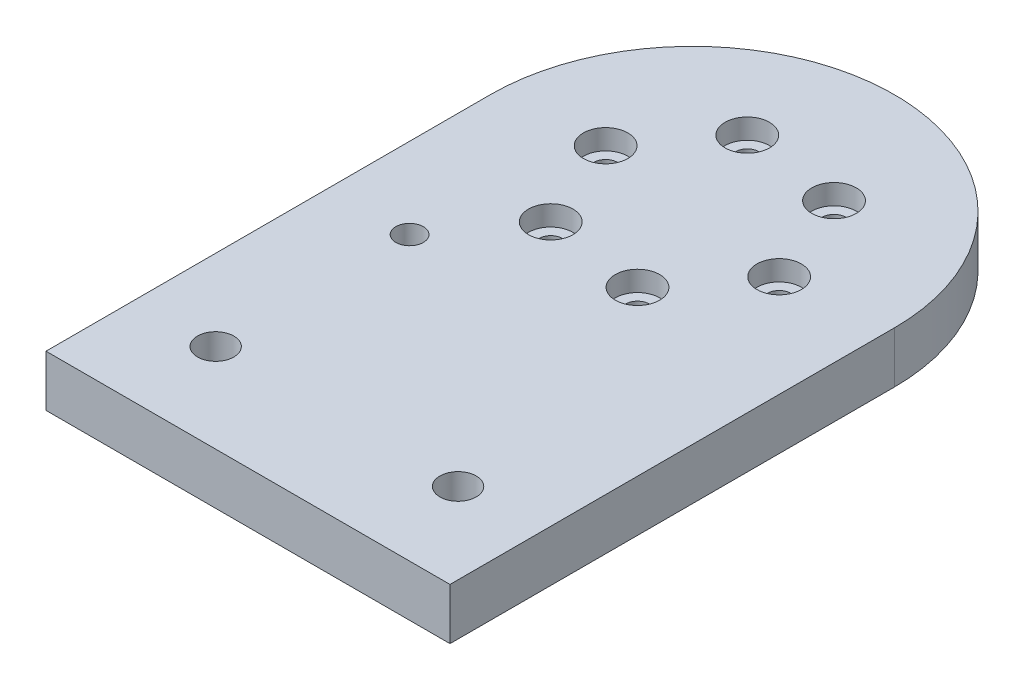
SolidWorks part; units mm, degrees
material "Aleación 6061"
ref_plane "Alzado" through (0, 0, 0) normal (0, 0, 1) x (1, 0, 0)
ref_plane "Planta" through (0, 0, 0) normal (0, 1, 0) x (1, 0, 0)
ref_plane "Vista lateral" through (0, 0, 0) normal (1, 0, 0) x (0, 0, -1)
sketch "Sk_Placa" plane through (0, 0, 0) normal (0, 1, 0) x (1, 0, 0)
  line L1 (-25, -526) -> (25, -526)
  line L2 (-25, -526) -> (-25, -490)
  line L3 (-25, -490) -> (25, -490)
  line L4 (25, -526) -> (25, -490)
  line L5 (-25, -526) -> (25, -490) construction
  line L6 (-25, -490) -> (25, -526) construction
  point P0 (0, -508)
  dimension "D1" = 50
  dimension "D2" = 36
  dimension "D3" = 508
extrude "Placa" add sketch "Sk_Placa" along normal blind 6.35 from offset 34.5
sketch "Sk_Extremo" plane through (0, 0, 0) normal (0, 1, 0) x (1, 0, 0)
  circle A0 centre (0, -490) radius 25
  dimension "D1" = 50
  dimension "D2" = 490
extrude "Extremo" add sketch "Sk_Extremo" along normal blind 6.35 from offset 34.5
sketch "Sk_Pasantes_M2-5_cubo_J5" plane through (0, 0, 0) normal (0, 1, 0) x (1, 0, 0)
  circle A0 centre (12.3902, -491.6532) radius 1.45
  circle A1 centre (4.7634, -501.5568) radius 1.45
  circle A2 centre (-7.6268, -499.9036) radius 1.45
  circle A3 centre (-12.3902, -488.3468) radius 1.45
  circle A4 centre (-4.7634, -478.4432) radius 1.45
  circle A5 centre (7.6268, -480.0964) radius 1.45
  dimension "D1" = 2.9
  dimension "D4" = 2.9
  dimension "D7" = 2.9
  dimension "D10" = 2.9
  dimension "D13" = 2.9
  dimension "D16" = 2.9
  dimension "D2" = 12.3902
  dimension "D3" = 491.6532
  dimension "D5" = 4.7634
  dimension "D6" = 501.5568
  dimension "D8" = 7.6268
  dimension "D9" = 499.9036
  dimension "D11" = 12.3902
  dimension "D12" = 488.3468
  dimension "D14" = 4.7634
  dimension "D15" = 478.4432
  dimension "D17" = 7.6268
  dimension "D18" = 480.0964
extrude "Pasantes_M2-5_cubo_J5" cut sketch "Sk_Pasantes_M2-5_cubo_J5" along normal blind 6.35 from offset 34.5
sketch "Sk_Cajas_M2-5_J5" plane through (0, 0, 0) normal (0, 1, 0) x (1, 0, 0)
  circle A0 centre (12.3902, -491.6532) radius 2.75
  circle A1 centre (4.7634, -501.5568) radius 2.75
  circle A2 centre (-7.6268, -499.9036) radius 2.75
  circle A3 centre (-12.3902, -488.3468) radius 2.75
  circle A4 centre (-4.7634, -478.4432) radius 2.75
  circle A5 centre (7.6268, -480.0964) radius 2.75
  dimension "D1" = 5.5
  dimension "D4" = 5.5
  dimension "D7" = 5.5
  dimension "D10" = 5.5
  dimension "D13" = 5.5
  dimension "D16" = 5.5
  dimension "D2" = 12.3902
  dimension "D3" = 491.6532
  dimension "D5" = 4.7634
  dimension "D6" = 501.5568
  dimension "D8" = 7.6268
  dimension "D9" = 499.9036
  dimension "D11" = 12.3902
  dimension "D12" = 488.3468
  dimension "D14" = 4.7634
  dimension "D15" = 478.4432
  dimension "D17" = 7.6268
  dimension "D18" = 480.0964
extrude "Cajas_M2-5_J5" cut sketch "Sk_Cajas_M2-5_J5" along normal blind 2.5 from offset 38.35
sketch "Sk_Extension_pestanas" plane through (0, 0, 0) normal (0, 1, 0) x (1, 0, 0)
  line L1 (-25, -545) -> (25, -545)
  line L2 (-25, -545) -> (-25, -526)
  line L3 (-25, -526) -> (25, -526)
  line L4 (25, -545) -> (25, -526)
  line L5 (-25, -545) -> (25, -526) construction
  line L6 (-25, -526) -> (25, -545) construction
  point P0 (0, -535.5)
  dimension "D1" = 50
  dimension "D2" = 19
  dimension "D3" = 535.5
extrude "Extension_pestanas" add sketch "Sk_Extension_pestanas" along normal blind 6.35 from offset 34.5
sketch "Sk_Pasantes_M4_repisa" plane through (0, 0, 0) normal (0, 1, 0) x (1, 0, 0)
  circle A0 centre (-15, -534) radius 2.25
  circle A1 centre (15, -534) radius 2.25
  dimension "D1" = 4.5
  dimension "D4" = 4.5
  dimension "D2" = 15
  dimension "D3" = 534
  dimension "D5" = 15
  dimension "D6" = 534
extrude "Pasantes_M4_repisa" cut sketch "Sk_Pasantes_M4_repisa" along normal blind 6.35 from offset 34.5
sketch "Sk_Pasante_M3_cincho" plane through (0, 0, 0) normal (0, 1, 0) x (1, 0, 0)
  circle A0 centre (-15, -510) radius 1.7
  dimension "D1" = 3.4
  dimension "D2" = 15
  dimension "D3" = 510
extrude "Pasante_M3_cincho" cut sketch "Sk_Pasante_M3_cincho" along normal blind 6.35 from offset 34.5
